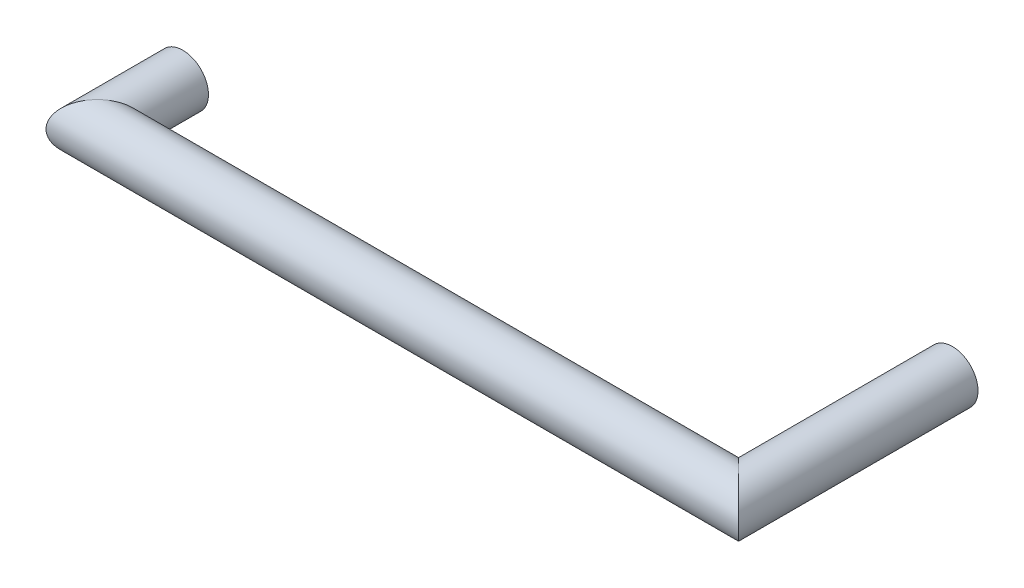
SolidWorks part; units mm, degrees
ref_plane "Front Plane" through (0, 0, 0) normal (0, 0, 1) x (1, 0, 0)
ref_plane "Top Plane" through (0, 0, 0) normal (0, 1, 0) x (1, 0, 0)
ref_plane "Right Plane" through (0, 0, 0) normal (1, 0, 0) x (0, 0, -1)
sketch "Sketch2" plane through (0, 0, 0) normal (0, 1, 0) x (1, 0, 0)
  line L0 (-7.5, 0) -> (7.5, 0)
  line L1 (-7.5, 0) -> (-7.5, 2)
  line L2 (7.5, 0) -> (7.5, 5)
  point P0 (-5, 2)
  point P4 (0, 0)
  dimension "D1" = 15
  dimension "D2" = 2
  dimension "D3" = 5
ref_plane "Plane1" through (-7.5, 0, -2) normal (0, 0, -1) x (-1, 0, 0)
sketch "Sketch3" plane through (-7.5, 0, -2) normal (0, 0, -1) x (-1, 0, 0)
  circle A1 centre (0, 0) radius 0.6
  point P0 (0, 0)
  dimension "D1" = 1.2
sweep "Sweep1" add profiles "Sketch3" path "Sketch2"
